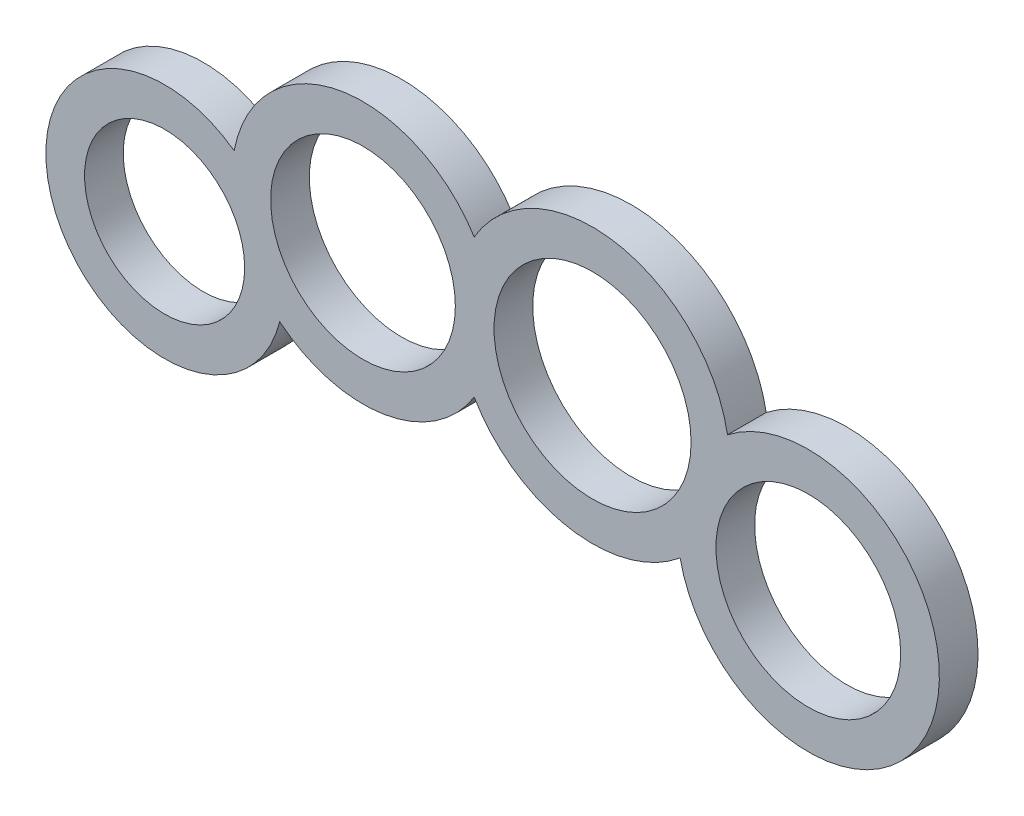
SolidWorks part; units mm, degrees
ref_plane "Front Plane" through (0, 0, 0) normal (0, 0, 1) x (1, 0, 0)
ref_plane "Top Plane" through (0, 0, 0) normal (0, 1, 0) x (1, 0, 0)
ref_plane "Right Plane" through (0, 0, 0) normal (1, 0, 0) x (0, 0, -1)
sketch "Sketch1" plane through (0, 0, 0) normal (0, 0, 1) x (1, 0, 0)
  line L0 (29.669, 0) -> (57.5488, -10.1474) construction
  line L1 (0, 0) -> (29.669, 0) construction
  line L2 (0, 0) -> (-25.6364, -9.3309) construction
  arc A0 (-10.7569, -13.082) -> (14.3696, -8.9646) centre (0, 0) ccw
  arc A1 (14.3696, -8.9646) -> (40.9797, -13.6567) centre (29.669, 0) ccw
  arc A2 (40.9797, -13.6567) -> (47.1119, 3.1913) centre (57.5488, -10.1474) ccw
  arc A3 (-16.6492, 3.107) -> (-10.7569, -13.082) centre (-25.6364, -9.3309) ccw
  arc A4 (14.3696, 8.9646) -> (-16.6492, 3.107) centre (0, 0) ccw
  arc A5 (47.1119, 3.1913) -> (14.3696, 8.9646) centre (29.669, 0) ccw
  dimension "D1" = 33.8732
  dimension "D3" = 35.4648
  dimension "D4" = 33.8732
  dimension "D8" = 30.6901
  dimension "D7" = 160
  dimension "D2" = 29.669
  dimension "D5" = 29.669
  dimension "D6" = 27.2817
  dimension "D9" = 160
extrude "Boss-Extrude2" add sketch "Sketch1" along normal blind 5
sketch "Sketch2" plane through (0, 0, 5) normal (0, 0, 1) x (1, 0, 0)
  circle A0 centre (-25.6364, -9.3309) radius 10.3451
  dimension "D1" = 20.6901
extrude "Cut-Extrude1" cut sketch "Sketch2" against normal blind 5
sketch "Sketch3" plane through (0, 0, 5) normal (0, 0, 1) x (1, 0, 0)
  circle A0 centre (0, 0) radius 11.9366
  dimension "D1" = 23.8732
extrude "Cut-Extrude2" cut sketch "Sketch3" against normal blind 5
sketch "Sketch5" plane through (0, 0, 5) normal (0, 0, 1) x (1, 0, 0)
  circle A0 centre (29.669, 0) radius 12.7324
  dimension "D1" = 25.4648
extrude "Cut-Extrude3" cut sketch "Sketch5" against normal blind 5
sketch "Sketch6" plane through (0, 0, 5) normal (0, 0, 1) x (1, 0, 0)
  circle A0 centre (57.5488, -10.1474) radius 11.9366
  dimension "D1" = 23.8732
extrude "Cut-Extrude4" cut sketch "Sketch6" against normal blind 5
